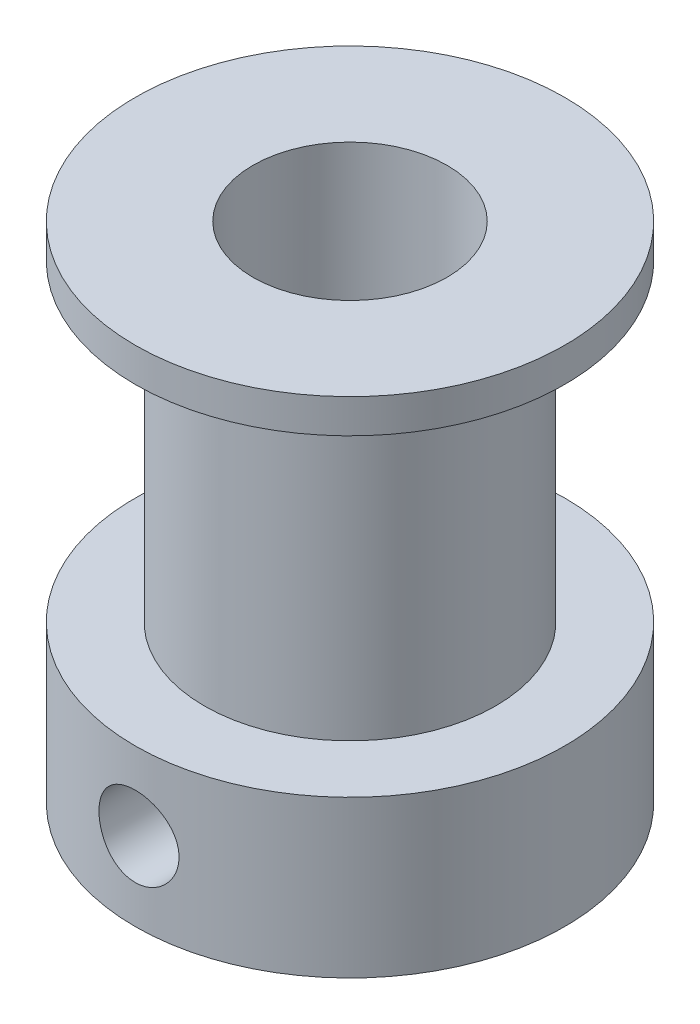
SolidWorks part; units mm, degrees
material "aluminio"
ref_plane "Alzado" through (0, 0, 0) normal (0, 0, 1) x (1, 0, 0)
ref_plane "Planta" through (0, 0, 0) normal (0, 1, 0) x (1, 0, 0)
ref_plane "Vista lateral" through (0, 0, 0) normal (1, 0, 0) x (0, 0, -1)
sketch "Croquis1" plane through (0, 0, 0) normal (0, 1, 0) x (1, 0, 0)
  circle A0 centre (0, 0) radius 8.85
  dimension "D1" = 17.7
extrude "Saliente-Extruir1" add sketch "Croquis1" along normal blind 6.45
sketch "Croquis2" plane through (0, 6.45, 0) normal (0, 1, 0) x (1, 0, 0)
  circle A0 centre (0, 0) radius 6
  dimension "D1" = 12
extrude "Saliente-Extruir2" add sketch "Croquis2" along normal blind 12.9
sketch "Croquis3" plane through (0, 19.35, 0) normal (0, 1, 0) x (1, 0, 0)
  circle A0 centre (0, 0) radius 8.85
  circle A1 centre (0, 0) radius 8.85 construction
extrude "Saliente-Extruir3" add sketch "Croquis3" along normal blind 1.4
sketch "Croquis4" plane through (0, 20.75, 0) normal (0, 1, 0) x (1, 0, 0)
  circle A0 centre (0, 0) radius 4
  dimension "D1" = 8
extrude "Cortar-Extruir1" cut sketch "Croquis4" against normal through all
sketch "Croquis5" plane through (0, 0, 0) normal (0, 0, 1) x (1, 0, 0)
  line L0 (0, 6.45) -> (0, 19.35)
  line L2 (-8.85, 19.35) -> (8.85, 19.35) construction
  line L3 (8.85, 6.45) -> (-8.85, 6.45) construction
  point P7 (0, 12.9)
hole_wizard "Taladro roscado M41 (falta definir posicio)" positions "Croquis7" profile "Croquis6" tap size "M4" standard "Iso"
sketch "Croquis7" plane through (0, 0, 0) normal (0, 0, 1) x (1, 0, 0)
  line L0 (0, 6.45) -> (0, 0) construction
  line L1 (8.85, 6.45) -> (-8.85, 6.45) construction
  point P7 (0, 3.225)
sketch "Croquis6" plane through (0, 3.225, 0) normal (1, 0, 0) x (0, 1, 0)
  line L0 (0, 0) -> (0, 8.851)
  line L1 (0, 8.851) -> (1.65, 8.851)
  line L2 (1.65, 8.851) -> (1.65, 0)
  line L5 (1.65, 0) -> (0, 0)
  line L11 (0, -6.35) -> (0, 107.95) construction
  dimension "Diámetro de perforador para roscar hasta el siguiente" = 3.3
  dimension "Profundidad de perforador para roscar hasta el siguiente" = 8.851
cosmetic thread "Rosca de taladro1" parameters "D2"=4
cosmetic thread "Rosca cosmética3" parameters "D2"=4
pattern_circular "MatrizC1" count 2 over 90 about axis through (0, 6.45, 0) along (0, -1, 0) of "Taladro roscado M41 (falta definir posicio)"
cosmetic thread "Rosca cosmética4"
